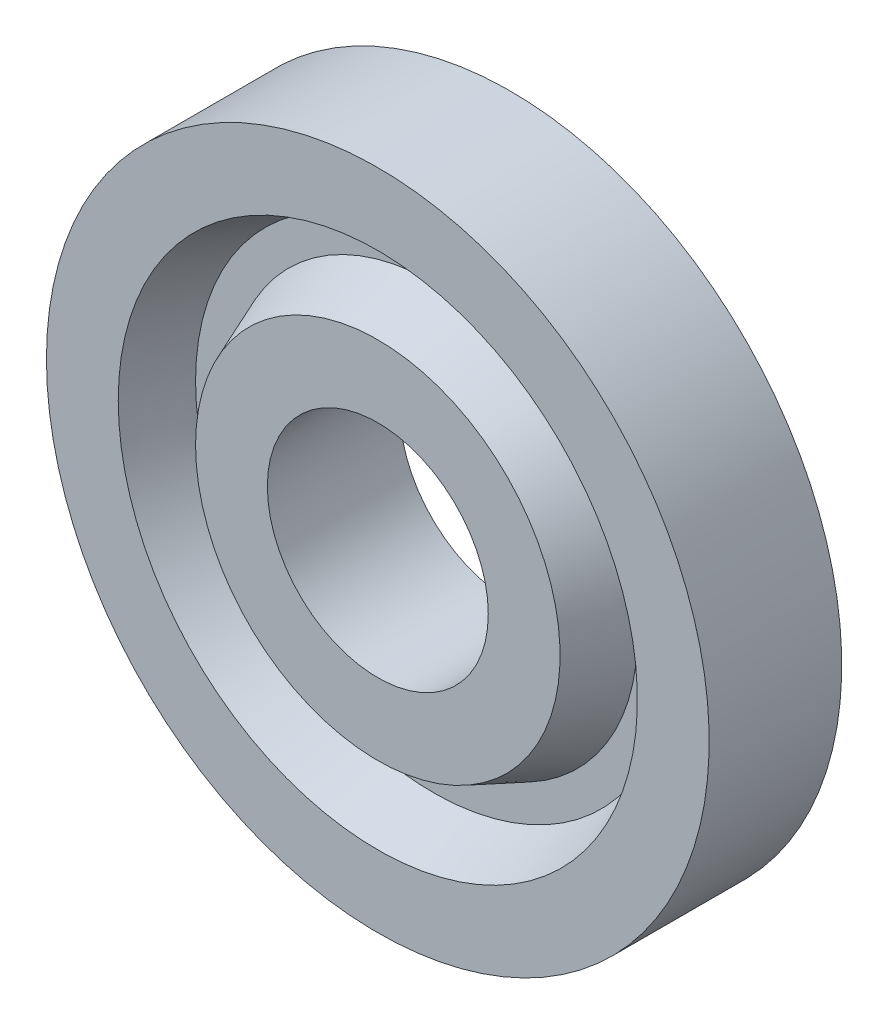
SolidWorks part; units mm, degrees
ref_plane "Front Plane" through (0, 0, 0) normal (0, 0, 1) x (1, 0, 0)
ref_plane "Top Plane" through (0, 0, 0) normal (0, 1, 0) x (1, 0, 0)
ref_plane "Right Plane" through (0, 0, 0) normal (1, 0, 0) x (0, 0, -1)
sketch "Sketch1" plane through (0, 0, 0) normal (0, 1, 0) x (1, 0, 0)
  line L0 (0, 28.9111) -> (0, -36.6207) construction
  line L2 (8.25, 3) -> (9.25, 0.5)
  line L3 (9.25, 0.5) -> (10.75, 0.5)
  line L4 (10.75, 0.5) -> (11.75, 3)
  line L6 (15, 3) -> (15, -3)
  line L8 (11.75, -3) -> (10.75, -0.5)
  line L9 (10.75, -0.5) -> (9.25, -0.5)
  line L10 (9.25, -0.5) -> (8.25, -3)
  line L12 (5, -3) -> (5, 3)
  line L13 (0, 0) -> (5, 0) construction
  line L14 (9.25, -0.5) -> (9.25, 0.5) construction
  line L15 (10.75, -0.5) -> (10.75, 0.5) construction
  line L16 (5, 3) -> (8.25, 3)
  line L17 (11.75, 3) -> (15, 3)
  line L18 (11.75, -3) -> (15, -3)
  line L19 (5, -3) -> (8.25, -3)
  line L20 (8.25, -3) -> (11.75, -3) construction
  line L21 (8.25, 3) -> (11.75, 3) construction
  line L22 (8.25, -3) -> (8.25, 3) construction
  line L23 (11.75, -3) -> (11.75, 3) construction
  dimension "D1" = 5
  dimension "D2" = 15
  dimension "D3" = 3.5
  dimension "D5" = 2.5
  dimension "D6" = 6
  dimension "D7" = 1.5
revolve "Revolve1" add sketch "Sketch1" angle 360 about L0
